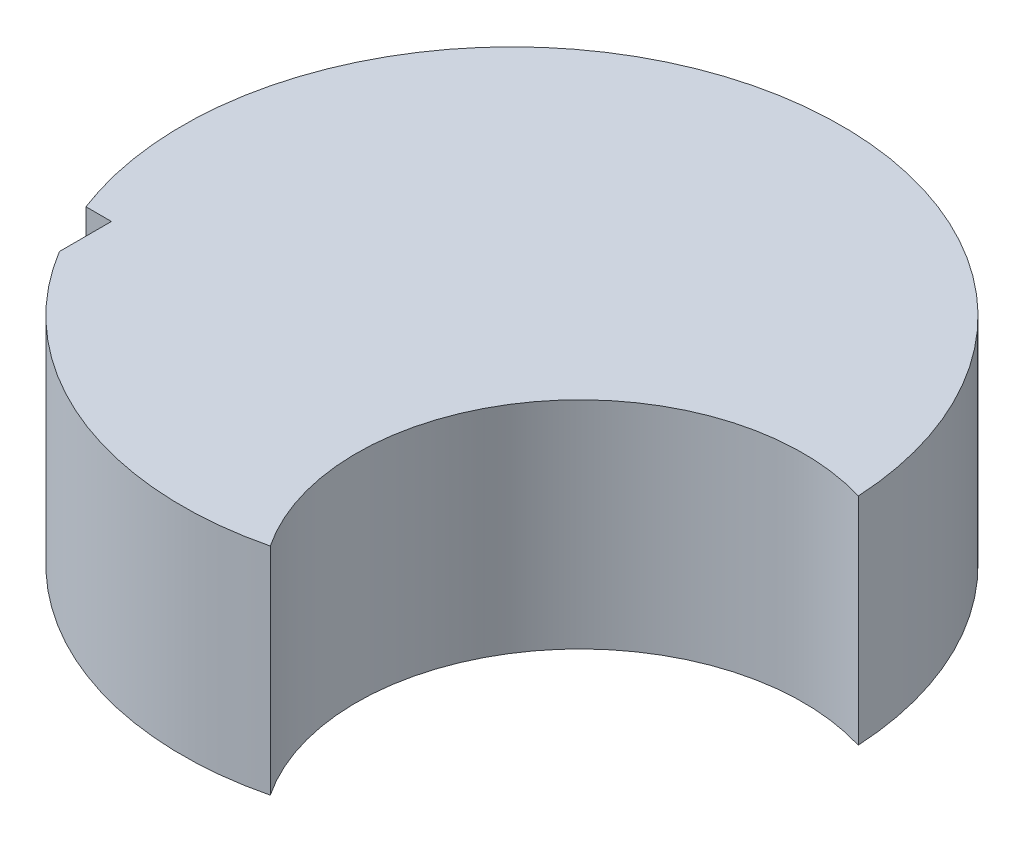
SolidWorks part; units mm, degrees
ref_plane "Front Plane" through (0, 0, 0) normal (0, 0, 1) x (1, 0, 0)
ref_plane "Top Plane" through (0, 0, 0) normal (0, 1, 0) x (1, 0, 0)
ref_plane "Right Plane" through (0, 0, 0) normal (1, 0, 0) x (0, 0, -1)
sketch "Sketch1" plane through (0, 0, 0) normal (0, 1, 0) x (1, 0, 0)
  arc A0 (92.9761, 4.8609) -> (22.1523, -90.4293) centre (0, 0) ccw
  arc A1 (92.9761, 4.8609) -> (22.1523, -90.4293) centre (74.7241, -55.5382) ccw
extrude "Boss-Extrude1" add sketch "Sketch1" along normal blind 60.96
ref_plane "Plane1" through (0, 137.16, 0) normal (0, 1, 0) x (1, 0, 0)
sketch "Sketch2" plane through (0, 137.16, 0) normal (0, 1, 0) x (1, 0, 0)
  point P0 (36.5712, 50.7694)
sketch "Sketch3" plane through (0, 60.96, 0) normal (0, 1, 0) x (1, 0, 0)
  line L1 (-120.6407, -33.4616) -> (-79.6791, -33.4616)
  line L2 (-120.6407, -33.4616) -> (-120.6407, -67.2117)
  line L3 (-120.6407, -67.2117) -> (-79.6791, -67.2117)
  line L4 (-79.6791, -33.4616) -> (-79.6791, -67.2117)
extrude "Cut-Extrude1" cut sketch "Sketch3" against normal up to next
